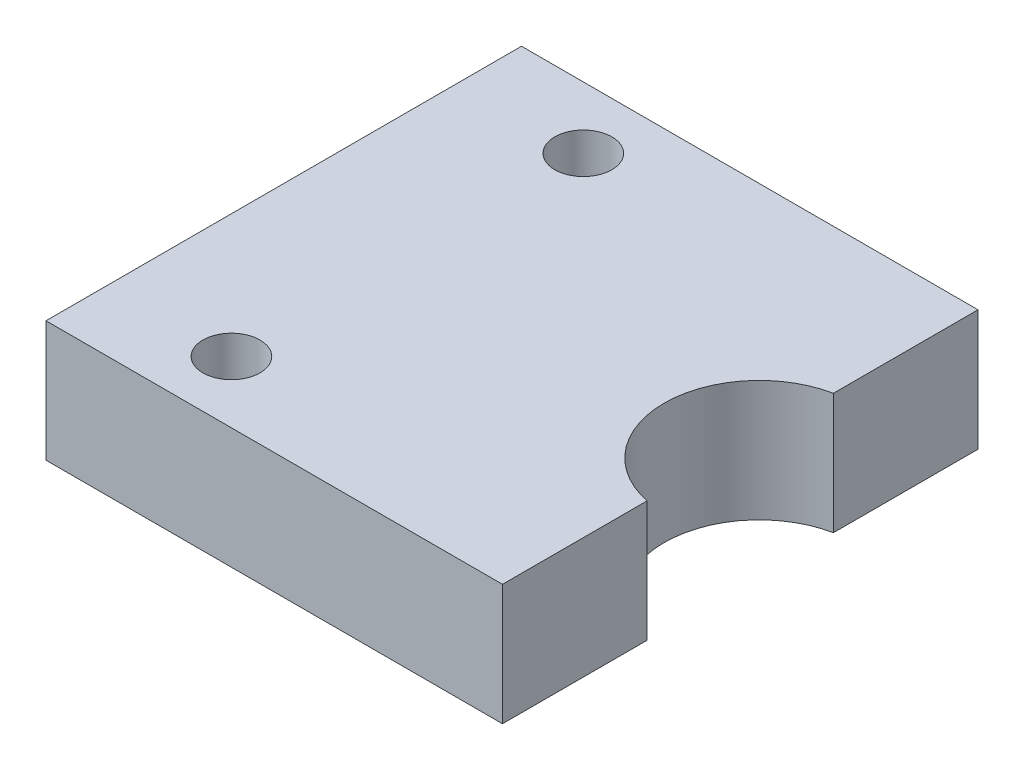
SolidWorks part; units mm, degrees
material "Aleación 6061"
ref_plane "Alzado" through (0, 0, 0) normal (0, 0, 1) x (1, 0, 0)
ref_plane "Planta" through (0, 0, 0) normal (0, 1, 0) x (1, 0, 0)
ref_plane "Vista lateral" through (0, 0, 0) normal (1, 0, 0) x (0, 0, -1)
sketch "Croquis2" plane through (0, 0, 0) normal (0, 1, 0) x (1, 0, 0)
  line L0 (-2, 25) -> (-50, 25)
  line L4 (-50, 25) -> (-50, -25)
  line L8 (-2, -25) -> (-2, -9.798)
  line L9 (-2, 9.798) -> (-2, 25)
  line L11 (-2, -25) -> (-50, -25)
  line L12 (0, 32.9631) -> (0, -34.8375) construction
  circle A0 centre (-37, -18.5) radius 3
  arc A2 (-2, 9.798) -> (-2, -9.798) centre (0, 0) ccw
  circle A5 centre (-37, 18.5) radius 3
  point P0 (0, 0)
  dimension "D3" = 25
  dimension "D4" = 10
  dimension "D6" = 6
  dimension "D7" = 6
  dimension "D9" = 13
  dimension "D1" = 50
  dimension "D2" = 48
extrude "Saliente-Extruir1" add sketch "Croquis2" along normal blind 12.7
